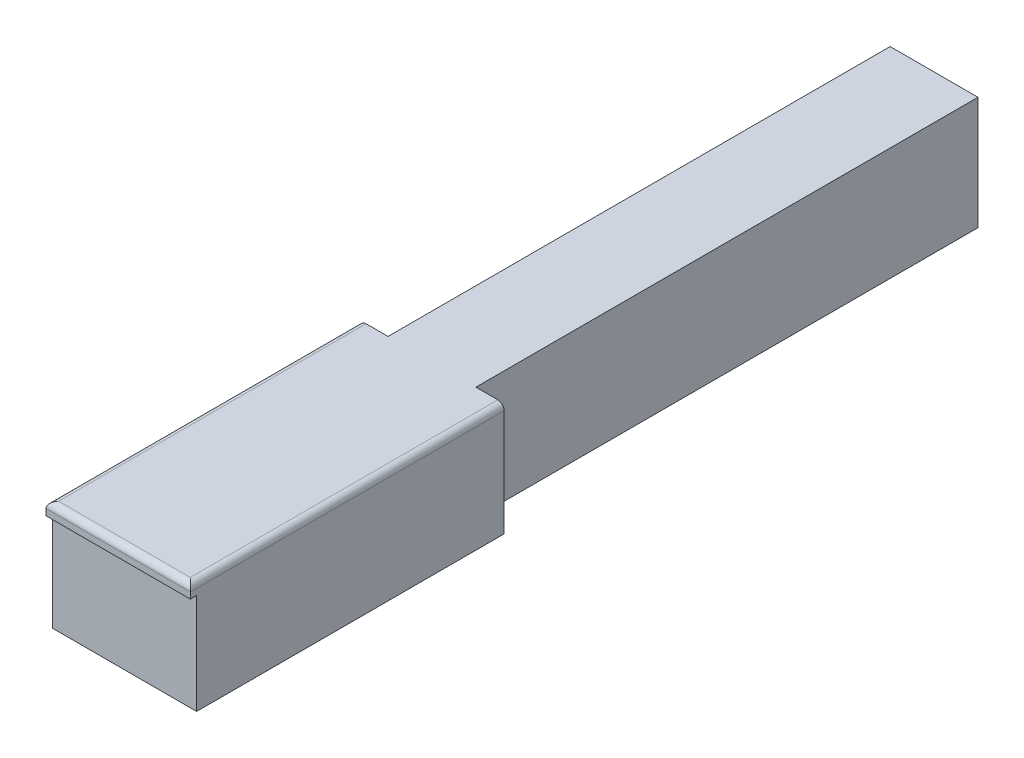
SolidWorks part; units mm, degrees
material "PF"
ref_plane "Alzado" through (0, 0, 0) normal (0, 0, 1) x (1, 0, 0)
ref_plane "Planta" through (0, 0, 0) normal (0, 1, 0) x (1, 0, 0)
ref_plane "Vista lateral" through (0, 0, 0) normal (1, 0, 0) x (0, 0, -1)
sketch "Croquis2" plane through (0, 0, 0) normal (0, 1, 0) x (1, 0, 0)
  line L1 (0, 0) -> (23, 0)
  line L2 (0, 0) -> (0, 130)
  line L3 (0, 130) -> (23, 130)
  line L4 (23, 0) -> (23, 130)
  line L5 (0, 130) -> (4.5, 130)
  line L6 (0, 115.866) -> (0, 50)
  line L7 (23, 50) -> (18.5, 50)
  line L8 (18.5, 130) -> (18.5, 50)
  line L9 (0, 50) -> (4.5, 50)
  line L10 (0, 130) -> (0, 50)
  line L11 (0, 50) -> (4.5, 50)
  line L12 (4.5, 130) -> (4.5, 50)
  dimension "D1" = 23
  dimension "D2" = 130
  dimension "D3" = 50
  dimension "D4" = 4.5
  dimension "D5" = 4.5
  dimension "D6" = 14
extrude "Saliente-Extruir1" add sketch "Croquis2" along normal blind 18 contours L8 L3 L2 L1 L4 L7
sketch "Croquis3" plane through (0, 0, 0) normal (0, 0, 1) x (1, 0, 0)
  line L0 (23, 18) -> (23, 0) construction
  line L1 (0, 0) -> (23, 0)
  line L2 (0, 0) -> (0, 16)
  line L3 (0, 16) -> (23, 16)
  line L4 (23, 0) -> (23, 16)
extrude "Cortar-Extruir1" cut sketch "Croquis3" against normal blind 1
fillet "Redondeo1" radius 1 3 edges at (11.5, 18, 0) (0, 18, -25) (23, 18, -25)
